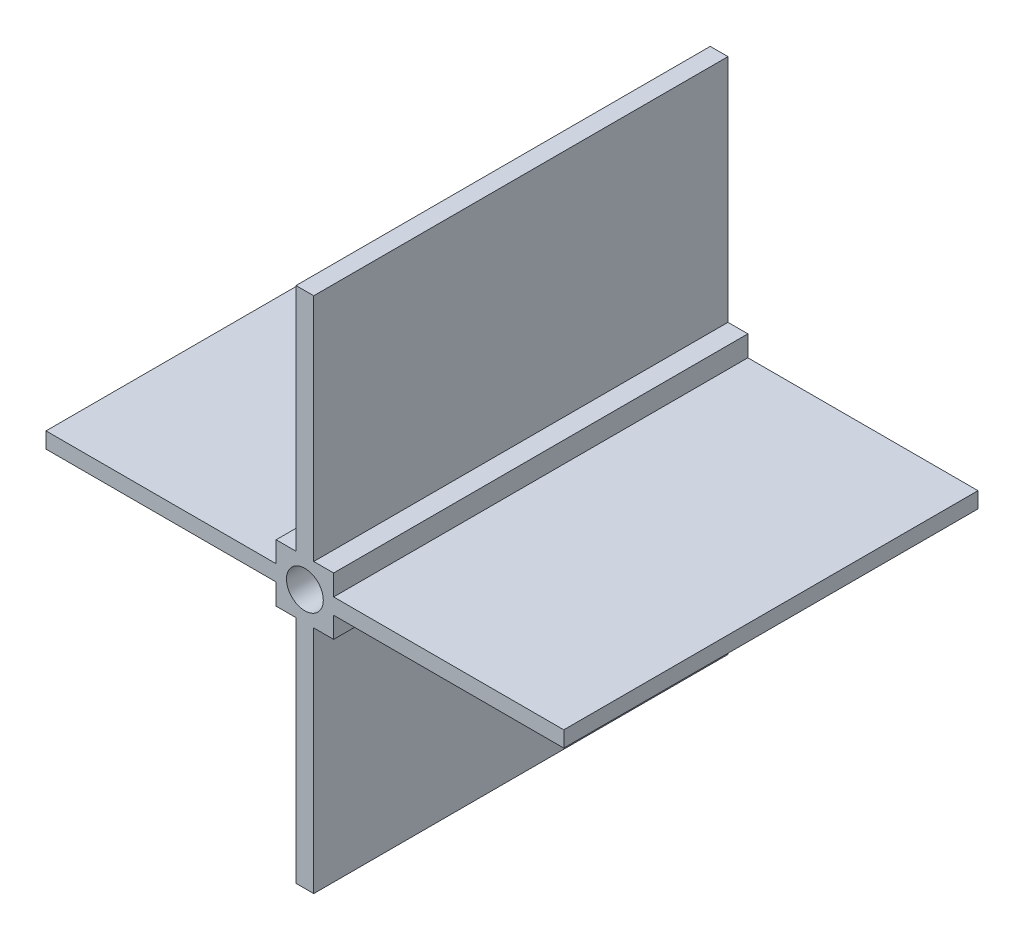
SolidWorks part; units mm, degrees
ref_plane "Front Plane" through (0, 0, 0) normal (0, 0, 1) x (1, 0, 0)
ref_plane "Top Plane" through (0, 0, 0) normal (0, 1, 0) x (1, 0, 0)
ref_plane "Right Plane" through (0, 0, 0) normal (1, 0, 0) x (0, 0, -1)
sketch "Sketch1" plane through (0, 0, 0) normal (0, 0, 1) x (1, 0, 0)
  line L0 (-3.175, 0.8841) -> (-3.175, 3.175)
  line L1 (-3.175, -3.175) -> (-0.9792, -3.175)
  line L2 (-3.175, -3.175) -> (-3.175, -0.8625)
  line L3 (-3.175, 3.175) -> (-0.9792, 3.175)
  line L4 (3.175, -3.175) -> (3.175, -0.8625)
  line L5 (-3.175, -3.175) -> (3.175, 3.175) construction
  line L6 (-3.175, 3.175) -> (3.175, -3.175) construction
  line L8 (-0.9792, 3.175) -> (-0.9792, 28.575)
  line L9 (-0.9792, 28.575) -> (0.978, 28.575)
  line L10 (0.978, 3.175) -> (0.978, 28.575)
  line L11 (3.175, 0.8841) -> (28.575, 0.8841)
  line L13 (3.175, -0.8625) -> (28.575, -0.8625)
  line L14 (28.575, 0.8841) -> (28.575, -0.8625)
  line L16 (-0.9792, -3.175) -> (-0.9792, -28.575)
  line L17 (-0.9792, -28.575) -> (0.978, -28.575)
  line L18 (0.978, -3.175) -> (0.978, -28.575)
  line L19 (-3.175, 0.8841) -> (-28.575, 0.8841)
  line L21 (-3.175, -0.8625) -> (-28.575, -0.8625)
  line L22 (-28.575, 0.8841) -> (-28.575, -0.8625)
  line L23 (3.175, 0.8841) -> (3.175, 3.175)
  line L24 (0.978, 3.175) -> (3.175, 3.175)
  line L25 (0.978, -3.175) -> (3.175, -3.175)
  point P0 (0, 0)
  dimension "D1" = 6.35
  dimension "D2" = 6.35
  dimension "D3" = 25.4
  dimension "D4" = 25.4
  dimension "D5" = 25.4
  dimension "D6" = 25.4
extrude "Boss-Extrude1" add sketch "Sketch1" along normal blind 45.72
sketch "Sketch2" plane through (0, 0, 45.72) normal (0, 0, 1) x (1, 0, 0)
  circle A0 centre (0, 0) radius 2.032
  dimension "D1" = 4.064
extrude "Cut-Extrude1" cut sketch "Sketch2" against normal blind 45.72
